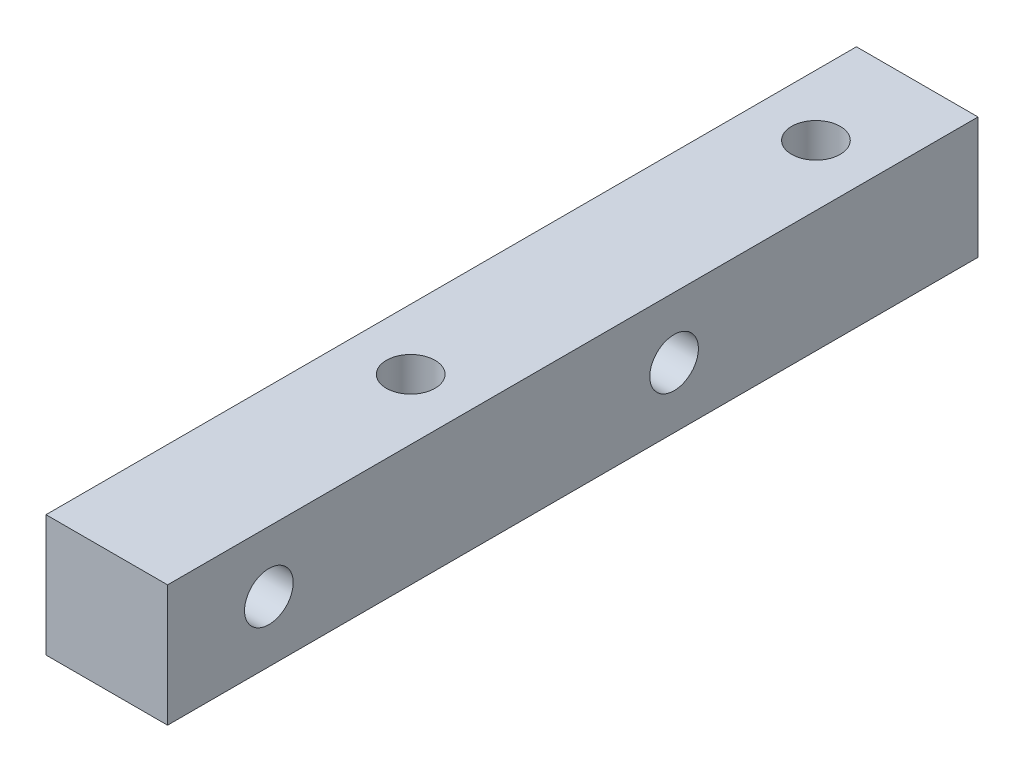
SolidWorks part; units mm, degrees
material "6061 合金"
ref_plane "前视基准面" through (0, 0, 0) normal (0, 0, 1) x (1, 0, 0)
ref_plane "上视基准面" through (0, 0, 0) normal (0, 1, 0) x (1, 0, 0)
ref_plane "右视基准面" through (0, 0, 0) normal (1, 0, 0) x (0, 0, -1)
ref_plane "基准面1" through (0, 0, 0) normal (-1, 0, 0) x (0, -1, 0)
sketch "草图1" plane through (0, 0, 0) normal (-1, 0, 0) x (0, -1, 0)
  line L0 (0, 0) -> (0, 40)
  line L1 (0, 40) -> (-6, 40)
  line L2 (-6, 40) -> (-6, 0)
  line L3 (-6, 0) -> (0, 0)
extrude "凸台-拉伸1" add sketch "草图1" against normal blind 6
hole_wizard "Ø2.4 (2.4) 直径孔1" positions "草图3" profile "草图2" hole size "Ø2.4" standard "ANSI Metric"
sketch "草图3" plane through (0, 6, 0) normal (0, 1, 0) x (1, 0, 0)
  point P0 (3, -5)
  point P1 (3, -25)
sketch "草图2" plane through (3, 6, 5) normal (1, 0, 0) x (0, 0, 1)
  line L0 (0, 0) -> (0, 6)
  line L1 (0, 6) -> (1.2, 6)
  line L2 (1.2, 6) -> (1.2, 0)
  line L5 (1.2, 0) -> (0, 0)
  line L11 (0, -6.35) -> (0, 107.95) construction
  dimension "通孔孔直径" = 2.4
  dimension "通孔孔深度" = 6
hole_wizard "Ø2.4 (2.4) 直径孔2" positions "草图5" profile "草图4" hole size "Ø2.4" standard "ANSI Metric"
sketch "草图5" plane through (0, 0, 0) normal (-1, 0, 0) x (0, 0, 1)
  point P0 (35, 3)
  point P1 (15, 3)
sketch "草图4" plane through (0, 3, 35) normal (0, 1, 0) x (0, 0, 1)
  line L0 (0, 0) -> (0, 6)
  line L1 (0, 6) -> (1.2, 6)
  line L2 (1.2, 6) -> (1.2, 0)
  line L5 (1.2, 0) -> (0, 0)
  line L11 (0, -6.35) -> (0, 107.95) construction
  dimension "通孔孔直径" = 2.4
  dimension "通孔孔深度" = 6
